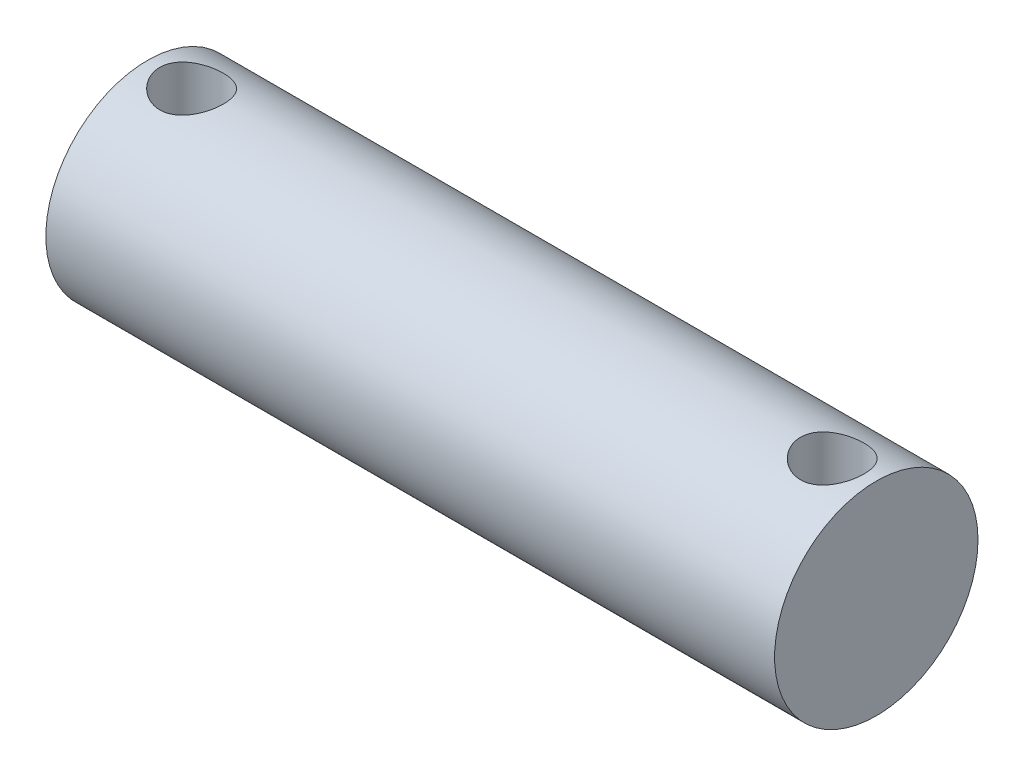
SolidWorks part; units mm, degrees
ref_plane "Alzado" through (0, 0, 0) normal (0, 0, 1) x (1, 0, 0)
ref_plane "Planta" through (0, 0, 0) normal (0, 1, 0) x (1, 0, 0)
ref_plane "Vista lateral" through (0, 0, 0) normal (1, 0, 0) x (0, 0, -1)
sketch "Croquis1" plane through (0, 0, 0) normal (1, 0, 0) x (0, 0, -1)
  circle A0 centre (0, 0) radius 12.7
  dimension "D1" = 25.4
extrude "Saliente-Extruir1" add sketch "Croquis1" along normal blind 91
sketch "Croquis2" plane through (0, 0, 0) normal (0, 1, 0) x (1, 0, 0)
  line L0 (0, 0) -> (5.5, 0) construction
  line L1 (45.5, -12.7) -> (45.5, 12.7) construction
  line L2 (0, -12.7) -> (91, -12.7) construction
  line L3 (91, 12.7) -> (0, 12.7) construction
  line L4 (91, 0) -> (85.5, 0) construction
  circle A0 centre (5.5, 0) radius 3.9687
  circle A1 centre (85.5, 0) radius 3.9688
  dimension "D2" = 7.9375
  dimension "D1" = 5.5
extrude "Cortar-Extruir1" cut sketch "Croquis2" against normal mid plane 40
